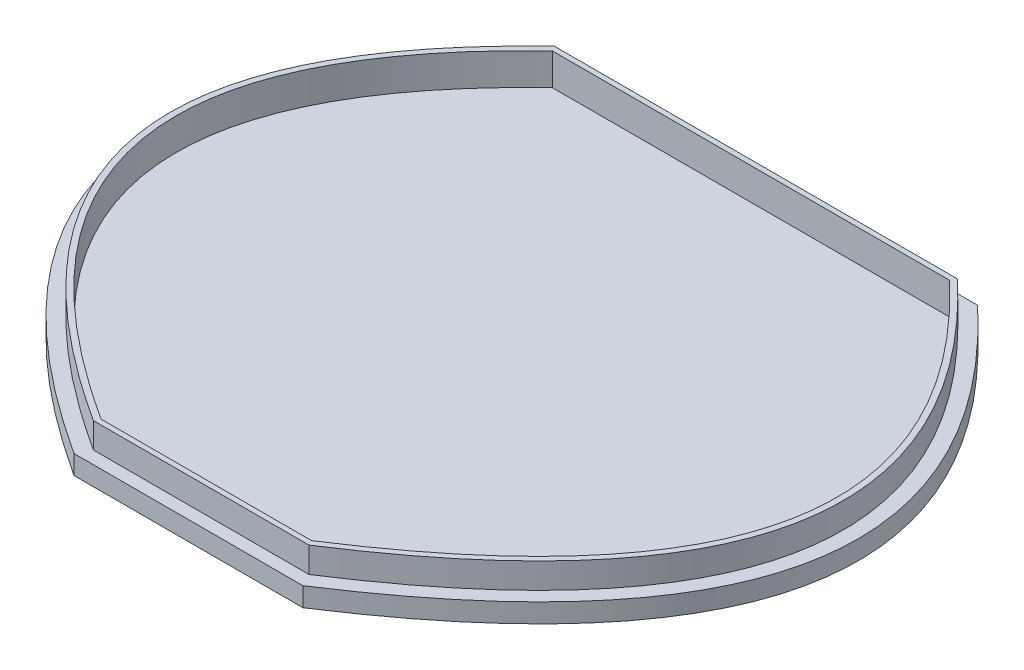
SolidWorks part; units mm, degrees
ref_plane "Front Plane" through (0, 0, 0) normal (0, 0, 1) x (1, 0, 0)
ref_plane "Top Plane" through (0, 0, 0) normal (0, 1, 0) x (1, 0, 0)
ref_plane "Right Plane" through (0, 0, 0) normal (1, 0, 0) x (0, 0, -1)
sketch "Sketch1" plane through (0, 0, 0) normal (0, 1, 0) x (1, 0, 0)
  line L0 (-13.7714, 11.3625) -> (17.9786, 11.3625)
  line L1 (17.9786, 11.3625) -> (2.1036, -16.1338)
  line L2 (2.1036, -16.1338) -> (-13.7714, 11.3625)
  line L3 (-21.3914, -1.8357) -> (-6.1514, 24.5607)
  line L4 (10.3586, 24.5607) -> (25.5986, -1.8357)
  line L5 (-6.1514, 24.5607) -> (10.3586, 24.5607)
  line L6 (-21.3914, -1.8357) -> (-8.0564, -24.9326)
  line L7 (-30.1737, 24.5607) -> (-30.1737, 11.3625) construction
  line L8 (8.7457, -4.6295) -> (20.1757, -11.2286) construction
  line L9 (-17.2639, -8.9848) -> (-5.8339, -2.3856) construction
  line L10 (12.2636, -24.9326) -> (25.5986, -1.8357)
  line L11 (11.6286, 22.361) -> (21.5273, 28.076) construction
  line L12 (21.5273, 28.076) -> (34.2273, 6.079) construction
  line L13 (34.2273, 6.079) -> (24.3286, 0.364) construction
  line L14 (2.1036, -16.1338) -> (2.1036, -33.7239) construction
  line L15 (-3.2905, -16.1338) -> (7.4978, -16.1338)
  line L16 (-8.0564, -24.9326) -> (12.2636, -24.9326)
  line L17 (21.5273, 28.076) -> (10.3586, 24.5607) construction
  line L18 (34.2273, 6.079) -> (25.5986, -1.8357) construction
  line L19 (10.0411, -2.3856) -> (15.1884, -5.3574)
  line L20 (2.1036, -16.1338) -> (2.1036, 0)
  line L21 (-7.4214, 22.361) -> (-17.32, 28.076) construction
  line L22 (-17.32, 28.076) -> (-30.02, 6.079) construction
  line L23 (-30.02, 6.079) -> (-20.1214, 0.364) construction
  line L24 (-30.02, 6.079) -> (-21.3914, -1.8357) construction
  line L25 (-17.32, 28.076) -> (-6.1514, 24.5607) construction
  line L26 (-17.32, 28.076) -> (21.5273, 28.076)
  line L27 (21.5273, 28.076) -> (34.2273, 6.079)
  line L28 (34.2273, 6.079) -> (12.2636, -24.9326)
  line L29 (-8.0564, -24.9326) -> (-30.02, 6.079)
  line L30 (-30.02, 6.079) -> (-17.32, 28.076)
  line L31 (-8.6475, -26.0756) -> (-31.3761, 6.0161)
  line L32 (-31.3761, 6.0161) -> (-17.9799, 29.219)
  line L33 (-17.9799, 29.219) -> (22.1872, 29.219)
  line L34 (22.1872, 29.219) -> (35.5834, 6.0161)
  line L35 (35.5834, 6.0161) -> (12.8547, -26.0756)
  line L36 (12.8547, -26.0756) -> (-8.6475, -26.0756)
  line L37 (-9.3043, -27.3456) -> (13.5115, -27.3456)
  line L38 (-9.3043, -27.3456) -> (-32.8829, 5.9463)
  line L39 (-8.9891, -25.5932) -> (-31.3761, 6.0161) construction
  line L40 (35.5834, 6.0161) -> (13.1964, -25.5932) construction
  line L42 (-32.8829, 5.9463) -> (-18.7132, 30.489)
  line L43 (-18.7132, 30.489) -> (22.9205, 30.489)
  line L44 (22.9205, 30.489) -> (37.0902, 5.9463)
  line L45 (37.0902, 5.9463) -> (13.5115, -27.3456)
  line L48 (-9.3043, -27.3456) -> (13.5115, -27.3456) construction
  line L49 (-8.6475, -26.0756) -> (12.8547, -26.0756) construction
  circle A0 centre (-15.0414, 0.3741) radius 1.27
  circle A1 centre (-3.6114, 19.4807) radius 1.27
  circle A2 centre (7.8186, 19.4807) radius 1.27
  circle A3 centre (19.2486, 0.3741) radius 1.27
  spline S0 degree 2 poles (-17.32, 28.076) (-46.8606, -0.0122) (-8.0564, -24.9326) knots 0 0 0 1 1 1
  spline S1 degree 2 poles (-17.9799, 29.219) (-48.95, -0.0801) (-8.6475, -26.0756) knots 0 0 0 1 1 1
  spline S2 degree 2 poles (-18.7132, 30.489) (-51.2716, -0.1555) (-9.3043, -27.3456) knots 0 0 0 1 1 1
  spline S3 degree 2 poles (21.5273, 28.076) (51.0679, -0.0122) (12.2636, -24.9326) knots 0 0 0 1 1 1
  spline S4 degree 2 poles (22.1872, 29.219) (53.1573, -0.0801) (12.8547, -26.0756) knots 0 0 0 1 1 1
  spline S5 degree 2 poles (22.9205, 30.489) (55.4788, -0.1555) (13.5115, -27.3456) knots 0 0 0 1 1 1
  point P43 (-5.8305, -29.134)
  point P44 (10.6795, -29.134)
  dimension "D23" = 2.54
  dimension "D25" = 2.54
  dimension "D28" = 2.54
  dimension "D31" = 2.54
  dimension "D1" = 31.75
  dimension "D2" = 31.75
  dimension "D3" = 31.75
  dimension "D4" = 60
  dimension "D5" = 60
  dimension "D6" = 30.48
  dimension "D7" = 30.48
  dimension "D8" = 20.32
  dimension "D9" = 13.1982
  dimension "D10" = 25.4
  dimension "D11" = 11.43
  dimension "D12" = 15.875
  dimension "D13" = 27.4963
  dimension "D14" = 7.62
  dimension "D15" = 7.62
  dimension "D16" = 13.1982
  dimension "D17" = 5.9436
  dimension "D18" = 13.0848
  dimension "D19" = 10.7764
  dimension "D20" = 15.875
  dimension "D21" = 15.875
  dimension "D22" = 60
  dimension "D24" = 6.35
  dimension "D26" = 2.54
  dimension "D27" = 5.08
  dimension "D29" = 2.54
  dimension "D30" = 5.08
  dimension "D32" = 25.4
  dimension "D34" = 15.24
  dimension "D35" = 7.62
  dimension "D37" = 8.7988
  dimension "D38" = 10.16
  dimension "D39" = 6.35
  dimension "D40" = 2.2098
  dimension "D41" = 2.2098
  dimension "D42" = 15.24
  dimension "D43" = 11.43
  dimension "D44" = 1.143
  dimension "D33" = 1.143
  dimension "D36" = 1.27
extrude "Boss-Extrude6" add sketch "Sketch1" along normal blind 1.27
sketch "Sketch2" plane through (0, 1.27, 0) normal (0, 1, 0) x (1, 0, 0)
  line L0 (-17.9799, 29.219) -> (22.1872, 29.219)
  line L1 (12.8547, -26.0756) -> (-8.6475, -26.0756)
  line L2 (-18.7132, 30.489) -> (22.9205, 30.489)
  line L3 (-9.3043, -27.3456) -> (13.5115, -27.3456)
  line L4 (-17.32, 28.076) -> (21.5273, 28.076)
  line L5 (21.5273, 28.076) -> (34.2273, 6.079)
  line L6 (34.2273, 6.079) -> (12.2636, -24.9326)
  line L7 (12.2636, -24.9326) -> (-8.0564, -24.9326)
  line L8 (-8.0564, -24.9326) -> (-30.02, 6.079)
  line L9 (-30.02, 6.079) -> (-17.32, 28.076)
  line L10 (-30.7734, 6.0441) -> (-17.6867, 28.711)
  line L11 (-17.6867, 28.711) -> (21.8939, 28.711)
  line L12 (21.8939, 28.711) -> (34.9807, 6.0441)
  line L13 (34.9807, 6.0441) -> (12.592, -25.5676)
  line L14 (12.592, -25.5676) -> (-8.3848, -25.5676)
  line L15 (-8.3848, -25.5676) -> (-30.7734, 6.0441)
  spline S0 degree 2 poles (-17.9799, 29.219) (-48.95, -0.0801) (-8.6475, -26.0756) knots 0 0 0 1 1 1
  spline S1 degree 2 poles (22.1872, 29.219) (53.1573, -0.0801) (12.8547, -26.0756) knots 0 0 0 1 1 1
  spline S2 degree 2 poles (-18.7132, 30.489) (-51.2716, -0.1555) (-9.3043, -27.3456) knots 0 0 0 1 1 1
  spline S3 degree 2 poles (22.9205, 30.489) (55.4788, -0.1555) (13.5115, -27.3456) knots 0 0 0 1 1 1
  spline S4 degree 2 poles (-17.6867, 28.711) (-48.0214, -0.0499) (-8.3848, -25.5676) knots 0 0 0 1 1 1
  spline S5 degree 2 poles (21.8939, 28.711) (52.2287, -0.0499) (12.592, -25.5676) knots 0 0 0 1 1 1
  spline M1 degree 2 poles (13.5115, -27.3456) (55.4788, -0.1555) (22.9205, 30.489) knots 0 0 0 1 1 1
  line M2 (22.9205, 30.489) -> (-18.7132, 30.489)
  spline M3 degree 2 poles (-18.7132, 30.489) (-51.2716, -0.1555) (-9.3043, -27.3456) knots 0 0 0 1 1 1
  line M4 (-9.3043, -27.3456) -> (13.5115, -27.3456)
  dimension "D1" = 0.635
extrude "Boss-Extrude7" add sketch "Sketch2" along normal blind 0.635 contours L0 S1 L1 S0 M4 M1 M2 M3 | S1 L0 S0 L1 L11 S5 L14 S4
sketch "Sketch3" plane through (0, 1.905, 0) normal (0, 1, 0) x (1, 0, 0)
  line L0 (-17.6867, 28.711) -> (21.8939, 28.711)
  line L1 (22.1872, 29.219) -> (-17.9799, 29.219)
  line L2 (-8.3848, -25.5676) -> (12.592, -25.5676)
  line L3 (12.8547, -26.0756) -> (-8.6475, -26.0756)
  spline S0 degree 2 poles (-17.9799, 29.219) (-48.95, -0.0801) (-8.6475, -26.0756) knots 0 0 0 1 1 1
  spline S1 degree 2 poles (-17.6867, 28.711) (-48.0214, -0.0499) (-8.3848, -25.5676) knots 0 0 0 1 1 1
  spline S2 degree 2 poles (22.1872, 29.219) (53.1573, -0.0801) (12.8547, -26.0756) knots 0 0 0 1 1 1
  spline S3 degree 2 poles (12.592, -25.5676) (52.2287, -0.0499) (21.8939, 28.711) knots 0 0 0 1 1 1
extrude "Boss-Extrude8" add sketch "Sketch3" along normal blind 2.54
